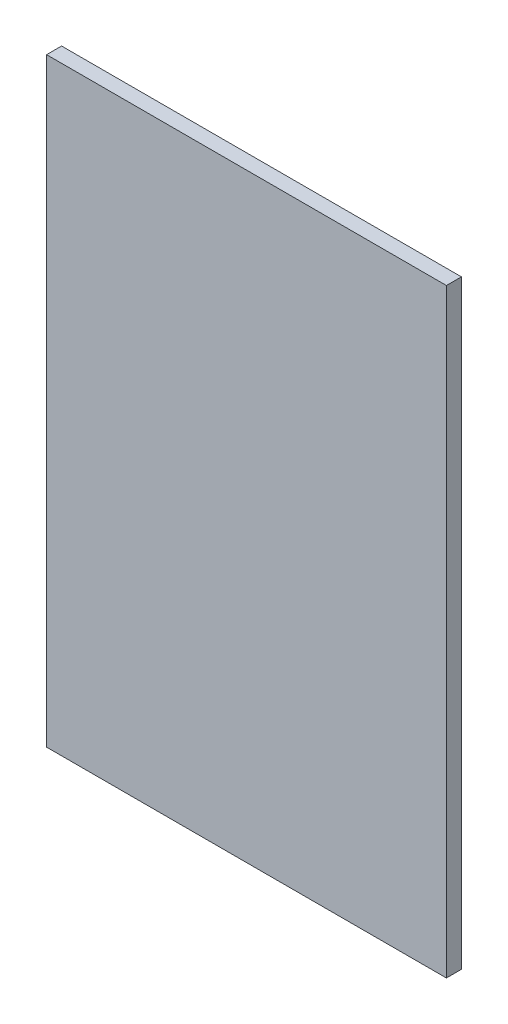
SolidWorks part; units mm, degrees
ref_plane "Ebene vorne" through (0, 0, 0) normal (0, 0, 1) x (1, 0, 0)
ref_plane "Ebene oben" through (0, 0, 0) normal (0, 1, 0) x (1, 0, 0)
ref_plane "Ebene rechts" through (0, 0, 0) normal (1, 0, 0) x (0, 0, -1)
sketch "Skizze1" plane through (0, 0, 0) normal (0, 0, 1) x (1, 0, 0)
  line L1 (-200, -300) -> (200, -300)
  line L2 (-200, -300) -> (-200, 300)
  line L3 (-200, 300) -> (200, 300)
  line L4 (200, -300) -> (200, 300)
  line L5 (-200, -300) -> (200, 300) construction
  line L6 (-200, 300) -> (200, -300) construction
  point P0 (0, 0)
  dimension "D1" = 400
  dimension "D2" = 600
extrude "Aufsatz-Linear austragen1" add sketch "Skizze1" along normal blind 15
